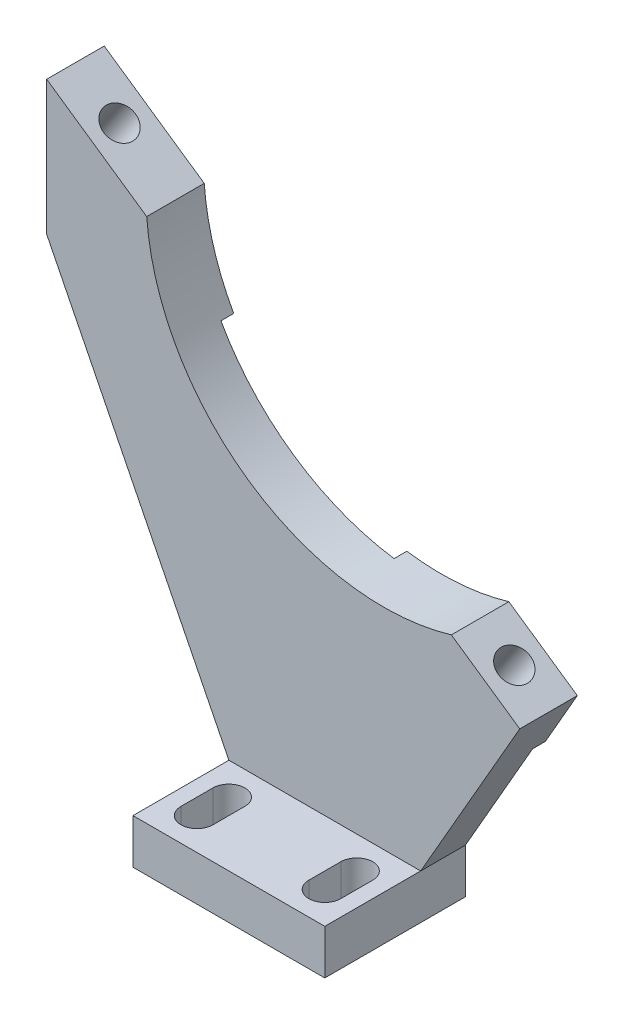
SolidWorks part; units mm, degrees
ref_plane "Front Plane" through (0, 0, 0) normal (0, 0, 1) x (1, 0, 0)
ref_plane "Top Plane" through (0, 0, 0) normal (0, 1, 0) x (1, 0, 0)
ref_plane "Right Plane" through (0, 0, 0) normal (1, 0, 0) x (0, 0, -1)
sketch "Sketch1" plane through (0, 0, 0) normal (0, 1, 0) x (1, 0, 0)
  line L0 (-12.5, -2.5) -> (-12.5, 2.5)
  line L1 (-15, 14.5) -> (15, 14.5)
  line L2 (-15, 14.5) -> (-15, -7.5)
  line L3 (-15, -7.5) -> (15, -7.5)
  line L4 (15, 14.5) -> (15, -7.5)
  line L5 (-7.5, -2.5) -> (-7.5, 2.5)
  line L6 (7.5, -2.5) -> (7.5, 2.5)
  line L7 (12.5, -2.5) -> (12.5, 2.5)
  line L8 (-10, 5) -> (-10, 2.5) construction
  line L9 (-10, 2.5) -> (-10, -2.5) construction
  line L10 (-10, -2.5) -> (-10, -5) construction
  line L11 (-10, 0) -> (-7.5, 0) construction
  line L12 (-7.5, 0) -> (0, 0) construction
  line L13 (0, 0) -> (7.5, 0) construction
  line L14 (-10, 2.5) -> (10, 2.5) construction
  line L15 (-15, 7.5) -> (15, 7.5) construction
  line L16 (-10, -2.5) -> (10, -2.5) construction
  line L17 (0, 0) -> (0, -7.5) construction
  line L18 (0, 0) -> (0, 7.5) construction
  circle A0 centre (-10, 2.5) radius 2.5
  circle A1 centre (-10, -2.5) radius 2.5
  circle A2 centre (10, 2.5) radius 2.5
  circle A3 centre (10, -2.5) radius 2.5
  dimension "D1" = 22
  dimension "D2" = 30
  dimension "D3" = 7
  dimension "D4" = 15
  dimension "D5" = 5
  dimension "D6" = 10
extrude "Boss-Extrude1" add sketch "Sketch1" along normal blind 7 contours L4 L1 L2 L3 A3 L6 A2 L7 A1 L0 A0 L5
sketch "Sketch2" plane through (0, 0, -14.5) normal (0, 0, -1) x (-1, 0, 0)
  line L0 (15, 7) -> (43.5, 64)
  line L1 (43.5, 64) -> (43.5, 85)
  line L2 (0, 0) -> (0, 41) construction
  line L3 (43.5, 85) -> (-30.5, 34)
  line L4 (-30.5, 34) -> (-15, 7)
  line L5 (15, 0) -> (-15, 0) construction
  line L6 (-30.5, 34) -> (-19.7959, 41.3771) construction
  line L7 (43.5, 85) -> (27.8556, 74.218) construction
  circle A0 centre (-9.2154, 77.0161) radius 37.1764
  line M10 (15, 7) -> (-15, 7)
  dimension "D1" = 34
  dimension "D2" = 64
  dimension "D3" = 85
  dimension "D4" = 74
  dimension "D5" = 15.5
  dimension "D6" = 41
  dimension "D7" = 13
  dimension "D8" = 19
extrude "Boss-Extrude2" add sketch "Sketch2" against normal blind 7 contours A0 L3 L4 L0 L1 M10
sketch "Sketch3" plane through (0, 0, -14.5) normal (0, 0, -1) x (-1, 0, 0)
  line L0 (-30.5, 34) -> (43.5, 85)
  line L1 (43.5, 85) -> (43.5, 72.8551)
  line L2 (43.5, 64) -> (43.5, 85) construction
  line L3 (43.5, 72.8551) -> (-25.5044, 25.298)
  line L4 (-30.5, 34) -> (-15, 7) construction
  line L5 (-25.5044, 25.298) -> (-30.5, 34)
  circle A0 centre (-9.2154, 77.0161) radius 37.1764
  arc A1 (-19.7959, 41.3771) -> (27.8556, 74.218) centre (-9.2154, 77.0161) ccw construction
  line M9 (43.5, 64) -> (43.5, 85)
  line M10 (43.5, 85) -> (27.8556, 74.218)
  arc M11 (27.8556, 74.218) -> (-19.7959, 41.3771) centre (-9.2154, 77.0161) cw
  line M12 (-19.7959, 41.3771) -> (-30.5, 34)
  line M13 (-30.5, 34) -> (-15, 7)
  dimension "D1" = 10
extrude "Boss-Extrude3" add sketch "Sketch3" along normal blind 2 contours L3 M11 M12 M13 | L3 M9 M10 M11
sketch "Sketch4" plane through (25.7084, 37.3023, 0) normal (0.5675, 0.8234, 0) x (0.8234, -0.5675, 0)
  line L0 (-75.6806, 12) -> (-0.6806, 12) construction
  line L1 (-52.563, 16.5) -> (-19.6703, 16.5) construction
  line L2 (-36.1167, 16.5) -> (-36.1167, 7.5) construction
  line L3 (-65.0528, 7.5) -> (-7.1806, 7.5) construction
  line L4 (-0.6806, 7.5) -> (-0.6806, 12) construction
  line L5 (-7.1806, 7.5) -> (5.8194, 7.5) construction
  line L6 (-0.6806, 12) -> (5.8194, 12) construction
  line L8 (5.8194, 7.5) -> (5.8194, 16.5) construction
  circle A0 centre (-75.6806, 12) radius 3 construction
  circle A1 centre (-0.6806, 12) radius 3 construction
  point P12 (-36.1167, 12)
  point P14 (5.8194, 12)
  point P22 (5.8194, 12)
  dimension "D1" = 6
  dimension "D2" = 75
hole_wizard "Tap Drill for M6x1.0 Tap2" positions "Sketch5" profile "Sketch6" hole size "M6x1.0" standard "ANSI Metric"
sketch "Sketch5" plane through (25.7084, 37.3023, 0) normal (0.5675, 0.8234, 0) x (0.8234, -0.5675, 0)
  point P0 (-75.6806, 12)
  point P3 (-0.6806, 12)
sketch "Sketch6" plane through (-36.6065, 80.249, -12) normal (0, 0, 1) x (-0.8234, 0.5675, 0)
  line L0 (0, 0) -> (0, 9.5022)
  line L1 (0, 9.5022) -> (2.5, 8)
  line L2 (2.5, 8) -> (2.5, 0)
  line L5 (2.5, 0) -> (0, 0)
  line L10 (0, 9.5022) -> (-2.5, 8) construction
  line L11 (0, -6.35) -> (0, 107.95) construction
  dimension "Hole Dia." = 5
  dimension "Hole Depth" = 8
  dimension "Drill Angle" = 118
